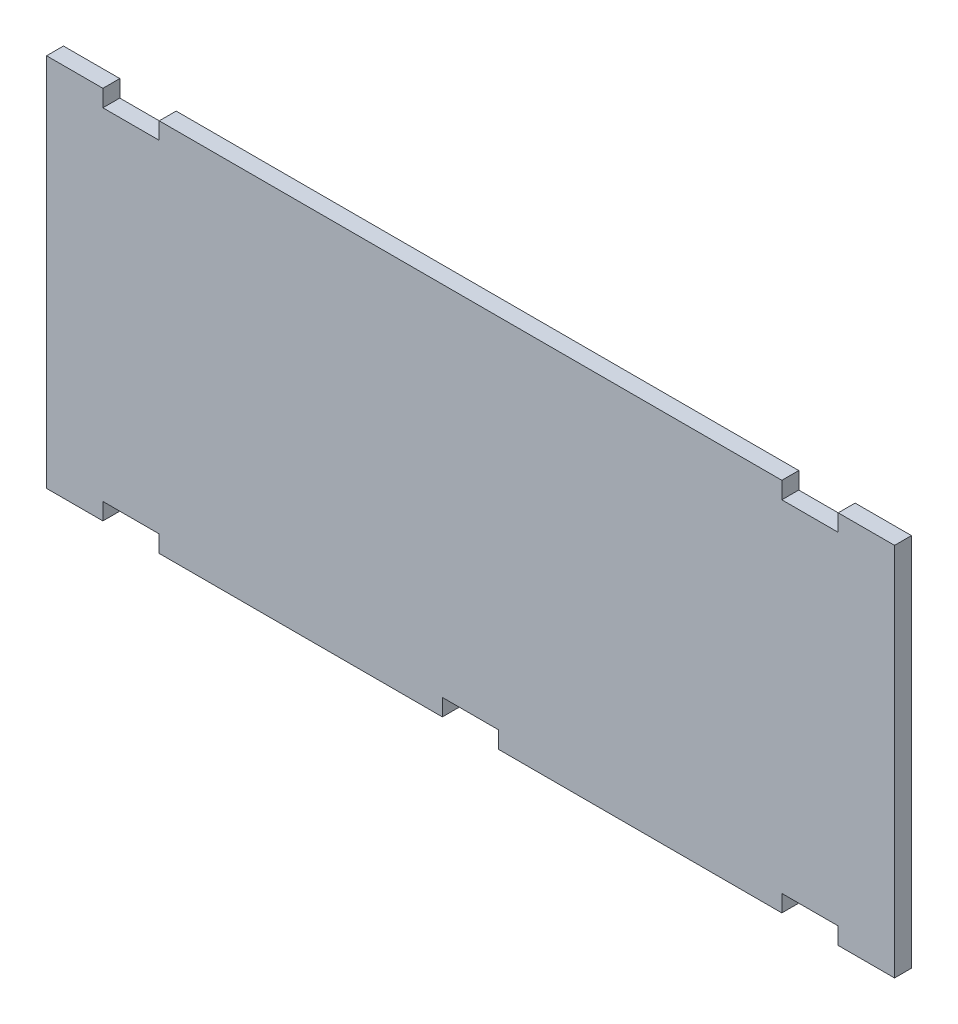
SolidWorks part; units mm, degrees
ref_plane "Plan de face" through (0, 0, 0) normal (0, 0, 1) x (1, 0, 0)
ref_plane "Plan de dessus" through (0, 0, 0) normal (0, 1, 0) x (1, 0, 0)
ref_plane "Plan de droite" through (0, 0, 0) normal (1, 0, 0) x (0, 0, -1)
sketch "Esquisse1" plane through (0, 0, 0) normal (0, 0, 1) x (1, 0, 0)
  line L0 (-301, 66.5) -> (0, 66.5) construction
  line L1 (-20, 0) -> (-20, 6)
  line L2 (0, 0) -> (0, 133)
  line L3 (0, 133) -> (-20, 133)
  line L4 (-301, 0) -> (-301, 133)
  line L5 (-281, 133) -> (-301, 133)
  line L6 (-281, 133) -> (-281, 127)
  line L7 (-281, 127) -> (-261, 127)
  line L8 (-261, 133) -> (-261, 127)
  line L9 (-40, 6) -> (-20, 6)
  line L10 (-40, 133) -> (-40, 127)
  line L11 (-40, 127) -> (-20, 127)
  line L12 (-20, 133) -> (-20, 127)
  line L13 (-40, 133) -> (-261, 133)
  line L14 (-40, 0) -> (-40, 6)
  line L15 (0, 0) -> (-20, 0)
  line L16 (-40, 0) -> (-140.5, 0)
  line L17 (-261, 0) -> (-261, 6)
  line L18 (-281, 6) -> (-261, 6)
  line L19 (-281, 0) -> (-301, 0)
  line L20 (-281, 0) -> (-281, 6)
  line L21 (-150.5, 6) -> (-150.5, 133) construction
  line L23 (-160.5, 0) -> (-160.5, 6)
  line L24 (-160.5, 6) -> (-140.5, 6)
  line L25 (-140.5, 0) -> (-140.5, 6)
  line L26 (-160.5, 0) -> (-261, 0)
  dimension "D1" = 133
  dimension "D2" = 301
  dimension "D3" = 6
  dimension "D4" = 6
  dimension "D5" = 20
  dimension "D6" = 20
  dimension "D7" = 20
  dimension "D8" = 20
  dimension "D9" = 20
  dimension "D10" = 10
  dimension "D11" = 6
extrude "Boss.-Extru.1" add sketch "Esquisse1" along normal blind 6
